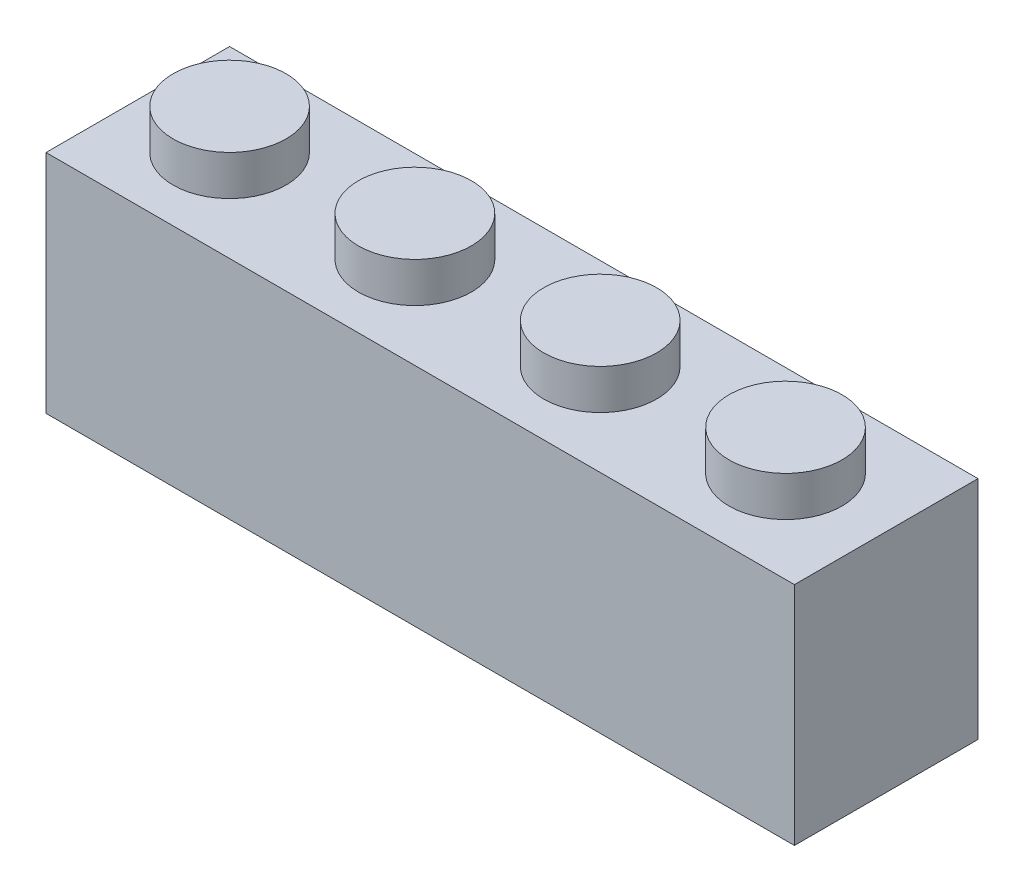
SolidWorks part; units mm, degrees
ref_plane "Спереди" through (0, 0, 0) normal (0, 0, 1) x (1, 0, 0)
ref_plane "Сверху" through (0, 0, 0) normal (0, 1, 0) x (1, 0, 0)
ref_plane "Справа" through (0, 0, 0) normal (1, 0, 0) x (0, 0, -1)
sketch "Эскиз1" plane through (0, 0, 0) normal (0, 1, 0) x (1, 0, 0)
  line L1 (15.9, -3.9) -> (-15.9, -3.9)
  line L2 (15.9, -3.9) -> (15.9, 3.9)
  line L3 (15.9, 3.9) -> (-15.9, 3.9)
  line L4 (-15.9, -3.9) -> (-15.9, 3.9)
  line L5 (15.9, -3.9) -> (-15.9, 3.9) construction
  line L6 (15.9, 3.9) -> (-15.9, -3.9) construction
  point P1 (0, 0)
  dimension "D1" = 31.8
  dimension "D2" = 7.8
extrude "Бобышка-Вытянуть1" add sketch "Эскиз1" along normal blind 9.6
sketch "Эскиз2" plane through (0, 9.6, 0) normal (0, 1, 0) x (1, 0, 0)
  line L0 (-15.9, 3.9) -> (-15.9, -3.9) construction
  line L1 (-15.9, -3.9) -> (15.9, -3.9) construction
  circle A0 centre (-12, 0) radius 2.4
  circle A1 centre (-4.126, 0) radius 2.4
  circle A2 centre (3.748, 0) radius 2.4
  circle A3 centre (11.622, 0) radius 2.4
  dimension "D1" = 3.9
  dimension "D2" = 3.9
  dimension "D3" = 4
extrude "Бобышка-Вытянуть2" add sketch "Эскиз2" along normal blind 1.7
sketch "Эскиз3" plane through (0, 0, 0) normal (0, -1, 0) x (1, 0, 0)
  line L0 (-15.9, -3.9) -> (-15.9, 3.9) construction
  line L1 (15.9, -3.9) -> (-15.9, -3.9) construction
  circle A0 centre (-12, 0) radius 2.5
  circle A1 centre (-4.126, 0) radius 2.5
  circle A2 centre (3.748, 0) radius 2.5
  circle A3 centre (11.622, 0) radius 2.5
  dimension "D1" = 3.9
  dimension "D2" = 3.9
  dimension "D3" = 4
extrude "Вырез-Вытянуть1" cut sketch "Эскиз3" against normal blind 1.8
